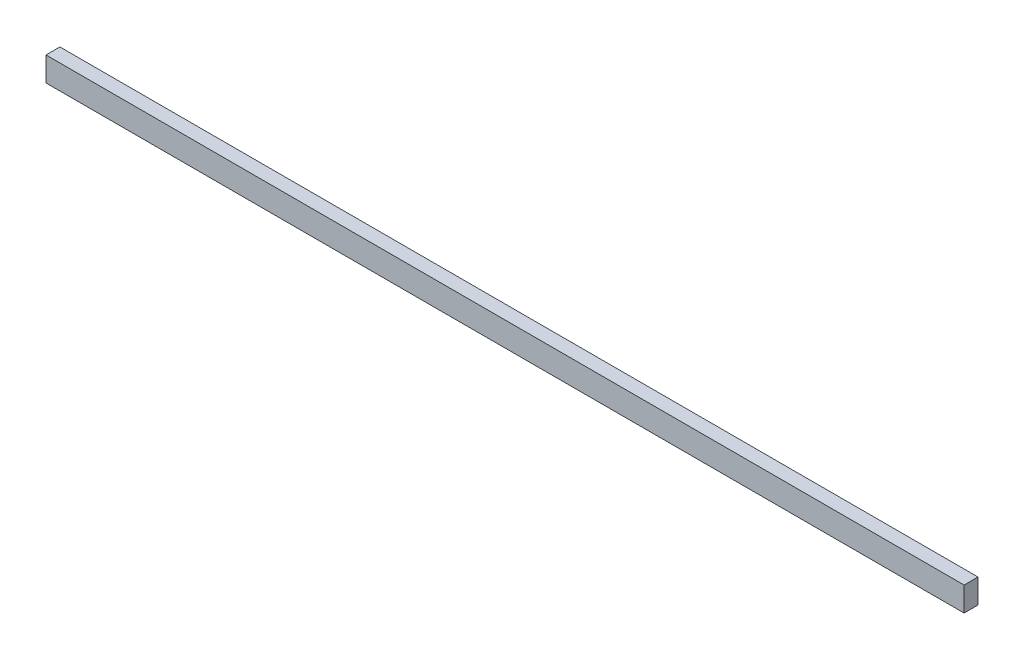
SolidWorks part; units mm, degrees
material "Pine"
ref_plane "Front Plane" through (0, 0, 0) normal (0, 0, 1) x (1, 0, 0)
ref_plane "Top Plane" through (0, 0, 0) normal (0, 1, 0) x (1, 0, 0)
ref_plane "Right Plane" through (0, 0, 0) normal (1, 0, 0) x (0, 0, -1)
sketch "Sketch1" plane through (0, 0, 0) normal (0, 0, 1) x (1, 0, 0)
  line L1 (-252.7054, -22.4037) -> (276.2946, -22.4037)
  line L2 (-252.7054, -22.4037) -> (-252.7054, -36.4037)
  line L3 (-252.7054, -36.4037) -> (276.2946, -36.4037)
  line L4 (276.2946, -22.4037) -> (276.2946, -36.4037)
  dimension "D1" = 529
  dimension "D2" = 14
extrude "Boss-Extrude1" add sketch "Sketch1" along normal blind 8 contours L1 L4 L3 L2
sketch "Sketch2" plane through (0, -36.4037, 0) normal (0, -1, 0) x (1, 0, 0)
  line L2 (-252.7054, 8) -> (276.2946, 8) construction
  line L3 (-252.7054, 8) -> (-252.7054, 0) construction
  line L4 (276.2946, 8) -> (276.2946, 0) construction
  circle A1 centre (-236.7054, 4) radius 2
  circle A2 centre (260.2946, 4) radius 2
  dimension "D1" = 4
  dimension "D4" = 4
  dimension "D2" = 4
  dimension "D3" = 16
  dimension "D5" = 16
extrude "Cut-Extrude1" cut sketch "Sketch2" against normal blind 10
